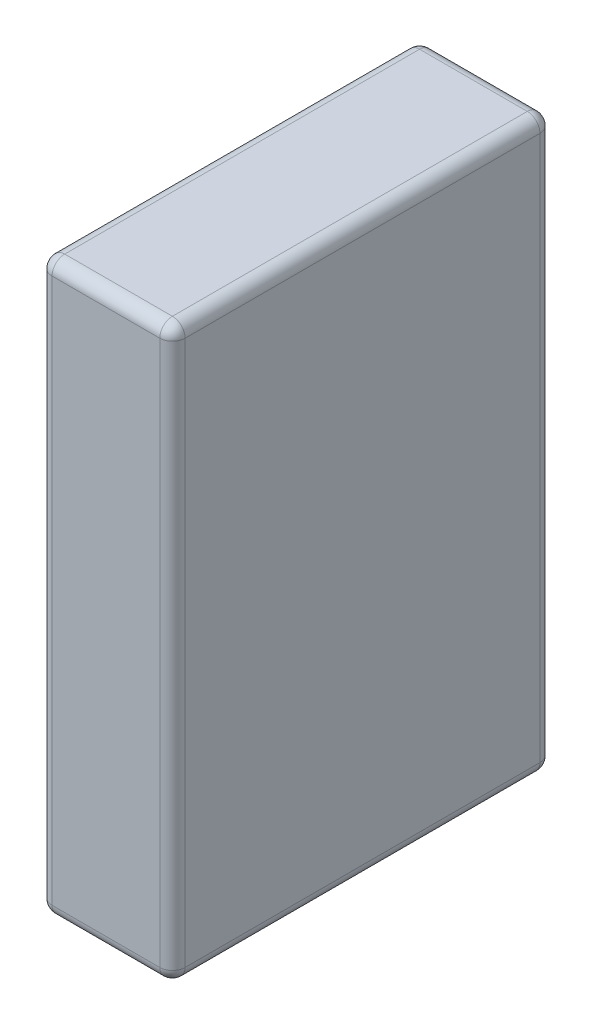
SolidWorks part; units mm, degrees
ref_plane "前视基准面" through (0, 0, 0) normal (0, 0, 1) x (1, 0, 0)
ref_plane "上视基准面" through (0, 0, 0) normal (0, 1, 0) x (1, 0, 0)
ref_plane "右视基准面" through (0, 0, 0) normal (1, 0, 0) x (0, 0, -1)
other "Configuration Table"
sketch "草图1" plane through (0, 0, 0) normal (1, 0, 0) x (0, 0, -1)
  line L1 (0, 0) -> (-60, 0)
  line L2 (0, 0) -> (0, -90)
  line L3 (0, -90) -> (-60, -90)
  line L4 (-60, 0) -> (-60, -90)
  dimension "D1" = 60
  dimension "D2" = 90
extrude "凸台-拉伸1" add sketch "草图1" along normal blind 21
sketch "草图2" plane through (0, 0, 0) normal (0, 0, -1) x (-1, 0, 0)
  line L0 (-21, 0) -> (0, 0) construction
  line L1 (-21, -90) -> (-21, 0) construction
  circle A0 centre (-10.5, -10) radius 2.5
  dimension "D1" = 5
  dimension "D2" = 10
  dimension "D3" = 10.5
extrude "切除-拉伸1" cut sketch "草图2" against normal blind 5
fillet "圆角2" radius 2 13 edges at (21, -45, 60) (21, 0, 30) (10.5, 0, 60) (10.5, -90, 60) (21, -90, 30) (10.5, -90, 0) (21, -45, 0) (10.5, 0, 0) (10.5, -7.5, 0) (0, 0, 30) (0, -45, 60) (0, -90, 30) (0, -45, 0)
